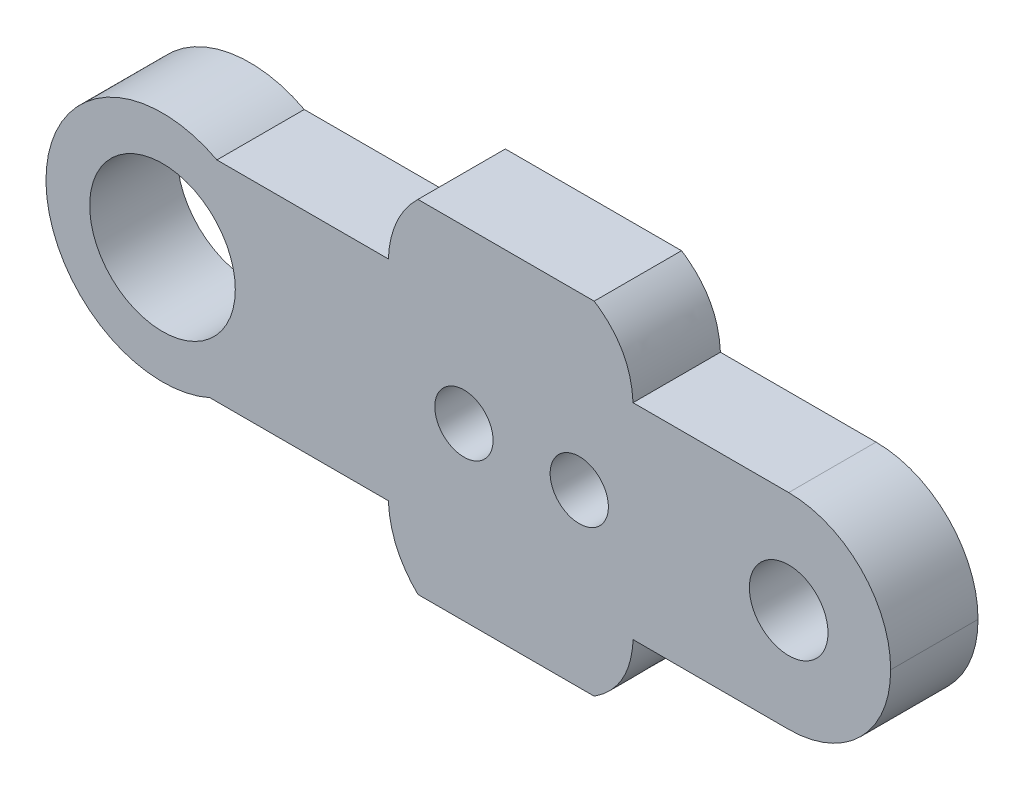
SolidWorks part; units mm, degrees
ref_plane "前视基准面" through (0, 0, 0) normal (0, 0, 1) x (1, 0, 0)
ref_plane "上视基准面" through (0, 0, 0) normal (0, 1, 0) x (1, 0, 0)
ref_plane "右视基准面" through (0, 0, 0) normal (1, 0, 0) x (0, 0, -1)
sketch "草图3" plane through (0, 0, 0) normal (0, 0, 1) x (1, 0, 0)
  line L0 (21.5, 3.5214) -> (16.1563, 3.5214)
  line L1 (1.8683, 3.5953) -> (7.7548, 3.5953)
  line L2 (8.7713, 5.8739) -> (14.8219, 5.8739)
  line L4 (8.7713, -5.8739) -> (14.8219, -5.8739)
  line L5 (1.628, -3.5953) -> (7.7548, -3.5953)
  line L6 (21.5, -3.5214) -> (16.1563, -3.5214)
  circle A0 centre (0, 0.0584) radius 2.5
  circle A1 centre (10.35, 0) radius 1
  circle A2 centre (14.31, 0) radius 1
  circle A3 centre (21.5, 0.0214) radius 1.35
  arc A4 (1.8683, 3.5953) -> (1.628, -3.5953) centre (0, 0.0584) ccw
  arc A5 (24.9999, 0) -> (21.5, 3.5214) centre (21.5, 0.0214) ccw
  arc A6 (24.9999, 0) -> (21.5, -3.5214) centre (21.5, -0.0214) cw
  spline S0 degree 2 poles (7.7548, 3.5953) (7.8164, 4.9447) (8.7713, 5.8739) knots 0 0 0 1 1 1
  spline S1 degree 2 poles (16.1563, 3.5214) (16.0882, 5.0515) (14.8219, 5.8739) knots 0 0 0 1 1 1
  spline S2 degree 2 poles (16.1563, -3.5214) (16.0882, -5.0515) (14.8219, -5.8739) knots 0 0 0 1 1 1
  spline S3 degree 2 poles (7.7548, -3.5953) (7.8164, -4.9447) (8.7713, -5.8739) knots 0 0 0 1 1 1
  dimension "D4" = 5
  dimension "D5" = 2
  dimension "D6" = 8
  dimension "D7" = 7
  dimension "D1" = 21.5
  dimension "D2" = 7.19
  dimension "D3" = 3.96
extrude "凸台-拉伸2" add sketch "草图3" along normal blind 3
